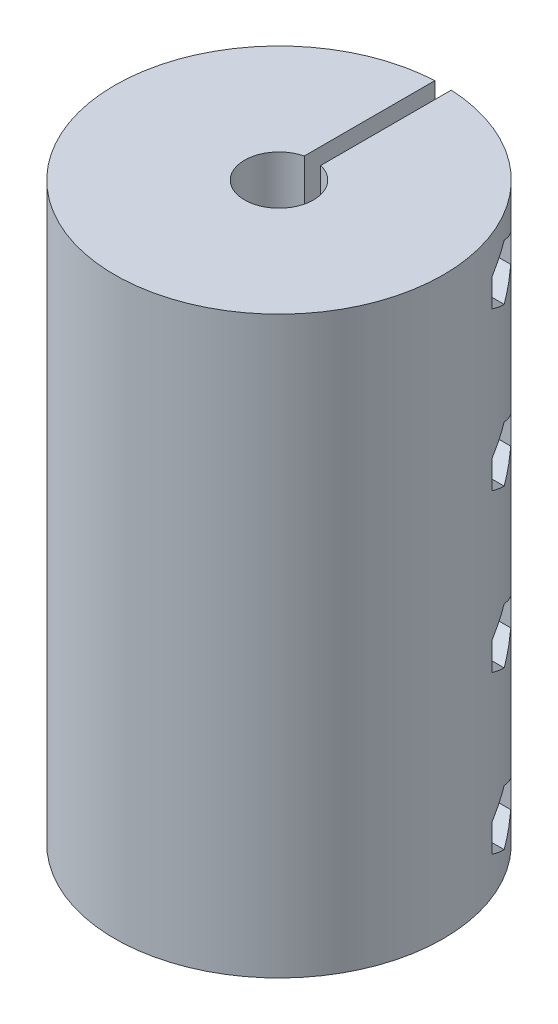
SolidWorks part; units mm, degrees
ref_plane "Front Plane" through (0, 0, 0) normal (0, 0, 1) x (1, 0, 0)
ref_plane "Top Plane" through (0, 0, 0) normal (0, 1, 0) x (1, 0, 0)
ref_plane "Right Plane" through (0, 0, 0) normal (1, 0, 0) x (0, 0, -1)
sketch "Sketch1" plane through (0, 0, 0) normal (0, 1, 0) x (1, 0, 0)
  circle A0 centre (0, 0) radius 20
  circle A1 centre (0, 0) radius 4.2
  dimension "D1" = 40
  dimension "D2" = 8.4
extrude "Boss-Extrude1" add sketch "Sketch1" along normal mid plane 70
sketch "Sketch2" plane through (0, 0, 0) normal (0, 1, 0) x (1, 0, 0)
  line L1 (-1, 0) -> (1, 0)
  line L2 (-1, 0) -> (-1, 25)
  line L3 (-1, 25) -> (1, 25)
  line L4 (1, 0) -> (1, 25)
  point P4 (0, 0)
  dimension "D1" = 2
  dimension "D2" = 0
  dimension "D3" = 25
extrude "Cut-Extrude1" cut sketch "Sketch2" against normal mid plane 70
ref_plane "Plane1" through (20, 0, 0) normal (1, 0, 0) x (0, 0, -1)
ref_plane "Plane2" through (-20, 0, 0) normal (1, 0, 0) x (0, 0, -1)
sketch "Sketch4" plane through (20, 0, 0) normal (1, 0, 0) x (0, 0, -1)
  line L0 (19.975, 35) -> (-20, 35) construction
  line L1 (-20, -35) -> (19.975, -35) construction
  circle A0 centre (10.2317, 28.75) radius 1.75
  circle A4 centre (10.2317, 9.5833) radius 1.75
  circle A5 centre (10.2317, -9.5833) radius 1.75
  circle A6 centre (10.2317, -28.75) radius 1.75
  point P10 (0, 0)
  dimension "D1" = 3.5
  dimension "D3" = 6.25
  dimension "D4" = 6.25
  dimension "D2" = 4
extrude "Cut-Extrude2" cut sketch "Sketch4" against normal blind 40
sketch "Sketch5" plane through (20, 0, 0) normal (1, 0, 0) x (0, 0, -1)
  line L0 (7.3067, 7.8946) -> (10.2317, 6.2058)
  line L1 (10.2317, 32.1275) -> (7.3067, 30.4387)
  line L2 (7.3067, 30.4387) -> (7.3067, 27.0613)
  line L3 (7.3067, 27.0613) -> (10.2317, 25.3725)
  line L4 (10.2317, 25.3725) -> (13.1567, 27.0613)
  line L5 (13.1567, 27.0613) -> (13.1567, 30.4387)
  line L6 (13.1567, 30.4387) -> (10.2317, 32.1275)
  line L7 (10.2317, 6.2058) -> (13.1567, 7.8946)
  line L8 (13.1567, 7.8946) -> (13.1567, 11.2721)
  line L9 (13.1567, 11.2721) -> (10.2317, 12.9608)
  line L10 (10.2317, 12.9608) -> (7.3067, 11.2721)
  line L11 (7.3067, 11.2721) -> (7.3067, 7.8946)
  line L12 (7.3067, -11.2721) -> (10.2317, -12.9608)
  line L13 (10.2317, -12.9608) -> (13.1567, -11.2721)
  line L14 (13.1567, -11.2721) -> (13.1567, -7.8946)
  line L15 (13.1567, -7.8946) -> (10.2317, -6.2058)
  line L16 (10.2317, -6.2058) -> (7.3067, -7.8946)
  line L17 (7.3067, -7.8946) -> (7.3067, -11.2721)
  line L18 (7.3067, -30.4387) -> (10.2317, -32.1275)
  line L19 (10.2317, -32.1275) -> (13.1567, -30.4387)
  line L20 (13.1567, -30.4387) -> (13.1567, -27.0613)
  line L21 (13.1567, -27.0613) -> (10.2317, -25.3725)
  line L22 (10.2317, -25.3725) -> (7.3067, -27.0613)
  line L23 (7.3067, -27.0613) -> (7.3067, -30.4387)
  line L24 (19.975, 35) -> (-20, 35) construction
  line L25 (-20, -35) -> (19.975, -35) construction
  circle A0 centre (10.2317, 28.75) radius 2.925 construction
  point P1 (13.1567, 28.75)
  dimension "D1" = 5.85
  dimension "D3" = 2.8725
  dimension "D4" = 2.8725
  dimension "D2" = 4
extrude "Cut-Extrude3" cut sketch "Sketch5" against normal blind 11
sketch "Sketch6" plane through (-20, 0, 0) normal (1, 0, 0) x (0, 0, -1)
  line L0 (-20, -35) -> (19.975, -35) construction
  circle A0 centre (10.2317, 28.75) radius 3
  circle A1 centre (10.2317, 9.5833) radius 3
  circle A2 centre (10.2317, -9.5833) radius 3
  circle A3 centre (10.2317, -28.75) radius 3
  dimension "D1" = 6
  dimension "D3" = 6.25
  dimension "D2" = 4
extrude "Cut-Extrude4" cut sketch "Sketch6" along normal blind 11
sketch "Sketch7" plane through (0, -35, 0) normal (0, -1, 0) x (1, 0, 0)
  circle A0 centre (0, 0) radius 3.1
  circle A1 centre (0, 0) radius 4.35
  dimension "D1" = 6.2
extrude "Boss-Extrude2" add sketch "Sketch7" against normal blind 35
sketch "Sketch8" plane through (0, -35, 0) normal (0, -1, 0) x (1, 0, 0)
  line L0 (-1, -10.2411) -> (-1, -1.3103)
  line L1 (-1, -19.975) -> (-1, -4.2335) construction
  line L2 (1, -10.2411) -> (1, -1.3103)
  line L3 (1, -4.2335) -> (1, -19.975) construction
  line L4 (1, -1.3103) -> (-1, -1.3103)
  line L5 (-1, -10.2411) -> (1, -10.2411)
extrude "Cut-Extrude5" cut sketch "Sketch8" against normal blind 50
